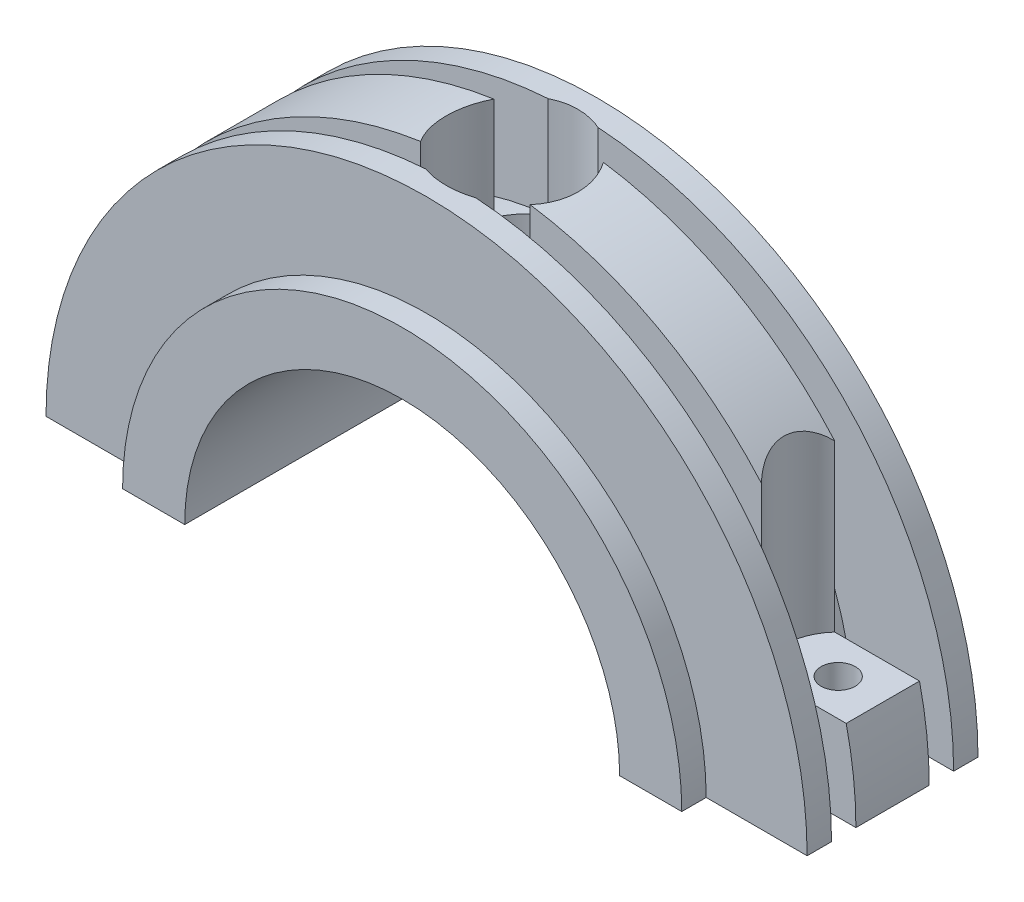
SolidWorks part; units mm, degrees
ref_plane "Front Plane" through (0, 0, 0) normal (0, 0, 1) x (1, 0, 0)
ref_plane "Top Plane" through (0, 0, 0) normal (0, 1, 0) x (1, 0, 0)
ref_plane "Right Plane" through (0, 0, 0) normal (1, 0, 0) x (0, 0, -1)
sketch "Sketch1" plane through (0, 0, 0) normal (0, 1, 0) x (1, 0, 0)
  line L0 (0, 0) -> (0, 12.5897) construction
  line L1 (-14, 0) -> (-14, 14.14)
  line L2 (-14, 14.14) -> (-18, 14.14)
  line L3 (-18, 14.14) -> (-18, 12.57)
  line L4 (-18, 12.57) -> (-24.5, 12.57)
  line L5 (-24.5, 12.57) -> (-24.5, 11)
  line L6 (-24.5, 11) -> (-18, 11)
  line L7 (-18, 11) -> (-18, 9.43)
  line L8 (-18, 9.43) -> (-24.5, 9.43)
  line L9 (-24.5, 9.43) -> (-24.5, 4.71)
  line L10 (-24.5, 4.71) -> (-18, 4.71)
  line L11 (-18, 4.71) -> (-18, 3.14)
  line L12 (-18, 3.14) -> (-24.5, 3.14)
  line L13 (-24.5, 3.14) -> (-24.5, 1.57)
  line L14 (-24.5, 1.57) -> (-18, 1.57)
  line L15 (-18, 1.57) -> (-18, 0)
  line L16 (-18, 0) -> (-14, 0)
  point P6 (-14, 7.07)
  dimension "D1" = 18
  dimension "D2" = 24.5
  dimension "D3" = 1.57
  dimension "D4" = 3.14
  dimension "D5" = 4.71
  dimension "D6" = 9.43
  dimension "D7" = 11
  dimension "D8" = 12.57
  dimension "D9" = 14.14
  dimension "D10" = 14
revolve "Revolve1" add sketch "Sketch1" angle 360 about L0
sketch "Sketch2" plane through (0, 0, 0) normal (0, 0, 1) x (1, 0, 0)
  line L0 (-24.5, 0) -> (24.5, 0)
  circle A0 centre (0, 0) radius 24.5 construction
  arc A1 (-24.5, 0) -> (24.5, 0) centre (0, 0) ccw
extrude "Cut-Extrude1" cut sketch "Sketch2" against normal through all
sketch "Sketch3" plane through (0, 0, 0) normal (0, 1, 0) x (1, 0, 0)
  line L0 (-24.5, 7.07) -> (24.5, 7.07) construction
  line L1 (-24.5, 9.43) -> (-24.5, 4.71) construction
  line L2 (24.5, 9.43) -> (24.5, 4.71) construction
  line L3 (0, 0) -> (0, 14.14) construction
  line L4 (18, 14.14) -> (-18, 14.14) construction
  line L5 (-23.5846, 9.43) -> (-24.5, 9.43)
  line L6 (24.5, 9.43) -> (-24.5, 9.43) construction
  line L8 (-24.5, 4.71) -> (-23.5846, 4.71)
  line L9 (-24.5, 4.71) -> (24.5, 4.71) construction
  line L10 (23.5846, 4.71) -> (24.5, 4.71)
  line L11 (24.5, 4.71) -> (24.5, 9.43)
  line L12 (24.5, 9.43) -> (23.5846, 9.43)
  line L13 (-24.5, 9.43) -> (-24.5, 4.71)
  arc A0 (-23.5846, 4.71) -> (-23.5846, 9.43) centre (-21, 7.07) ccw
  arc A1 (23.5846, 4.71) -> (23.5846, 9.43) centre (21, 7.07) cw
  dimension "D1" = 7
  dimension "D2" = 21
extrude "Cut-Extrude2" cut sketch "Sketch3" along normal through all from offset 5.5
sketch "Sketch4" plane through (0, 0, 0) normal (0, -1, 0) x (1, 0, 0)
  line L0 (-24.5, -7.07) -> (24.5, -7.07) construction
  line L1 (-24.5, -9.43) -> (-24.5, -4.71) construction
  line L2 (24.5, -9.43) -> (24.5, -4.71) construction
  circle A0 centre (-21, -7.07) radius 1.1
  circle A1 centre (21, -7.07) radius 1.1
  circle A2 centre (0, -7.07) radius 4.245
  dimension "D1" = 2.2
  dimension "D2" = 2.2
  dimension "D5" = 8.49
  dimension "D3" = 21
  dimension "D4" = 21
extrude "Cut-Extrude3" cut sketch "Sketch4" against normal through all
